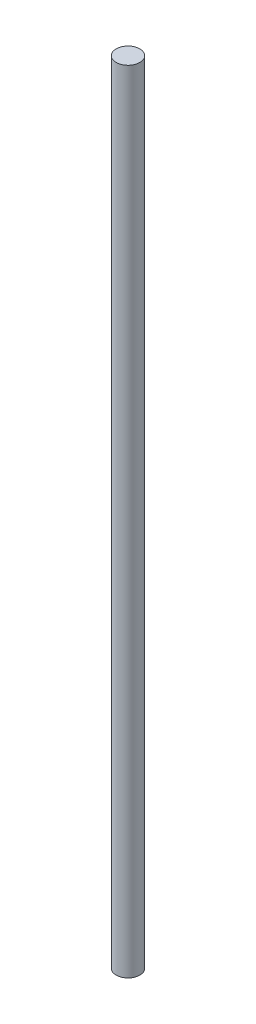
SolidWorks part; units mm, degrees
ref_plane "Спереди" through (0, 0, 0) normal (0, 0, 1) x (1, 0, 0)
ref_plane "Сверху" through (0, 0, 0) normal (0, 1, 0) x (1, 0, 0)
ref_plane "Справа" through (0, 0, 0) normal (1, 0, 0) x (0, 0, -1)
sketch "Эскиз1" plane through (0, 0, 0) normal (0, 1, 0) x (1, 0, 0)
  circle A0 centre (0, 0) radius 1.5
extrude "Бобышка-Вытянуть1" add sketch "Эскиз1" along normal blind 100.4
